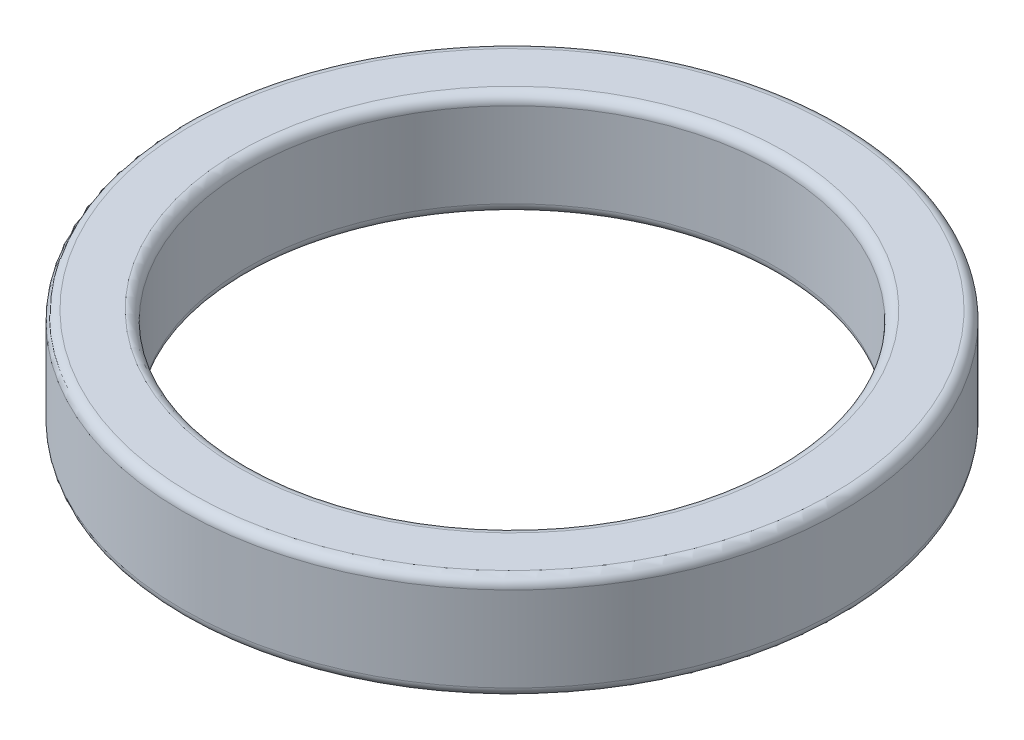
SolidWorks part; units mm, degrees
ref_plane "Front Plane" through (0, 0, 0) normal (0, 0, 1) x (1, 0, 0)
ref_plane "Top Plane" through (0, 0, 0) normal (0, 1, 0) x (1, 0, 0)
ref_plane "Right Plane" through (0, 0, 0) normal (1, 0, 0) x (0, 0, -1)
sketch "Sketch1" plane through (0, 0, 0) normal (0, 1, 0) x (1, 0, 0)
  circle A0 centre (0, 0) radius 4
  circle A1 centre (0, 0) radius 5
  dimension "D1" = 8
  dimension "D2" = 10
extrude "Boss-Extrude1" add sketch "Sketch1" along normal blind 1.5875
fillet "Fillet1" radius 0.15 4 edges at (0, 1.5875, 4) (0, 1.5875, 5) (0, 0, 4) (0, 0, 5)
